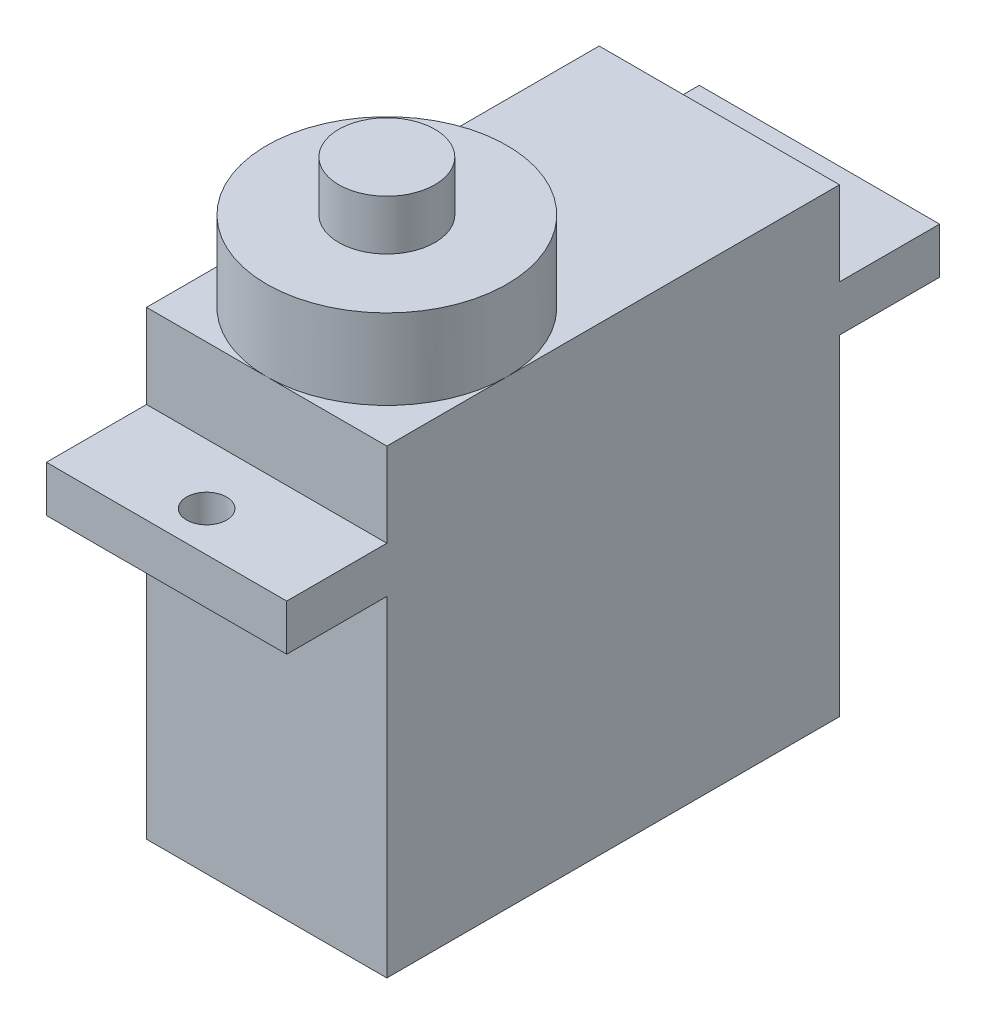
SolidWorks part; units mm, degrees
ref_plane "Front Plane" through (0, 0, 0) normal (0, 0, 1) x (1, 0, 0)
ref_plane "Top Plane" through (0, 0, 0) normal (0, 1, 0) x (1, 0, 0)
ref_plane "Right Plane" through (0, 0, 0) normal (1, 0, 0) x (0, 0, -1)
sketch "Sketch1" plane through (0, 0, 0) normal (1, 0, 0) x (0, 0, -1)
  line L1 (0, 0) -> (22.6, 0)
  line L2 (0, 0) -> (0, 23)
  line L3 (0, 23) -> (22.6, 23)
  line L4 (22.6, 0) -> (22.6, 23)
  dimension "D1" = 23
  dimension "D2" = 22.6
extrude "Boss-Extrude1" add sketch "Sketch1" along normal blind 12
sketch "Sketch2" plane through (0, 23, 0) normal (0, 1, 0) x (1, 0, 0)
  line L0 (12, 22.6) -> (12, 0) construction
  line L1 (-6.6, 0) -> (6.6, 0) construction
  circle A0 centre (6, 6) radius 6
  dimension "D1" = 12
  dimension "D3" = 6
  dimension "D2" = 6
extrude "Boss-Extrude2" add sketch "Sketch2" along normal blind 4
sketch "Sketch3" plane through (0, 27, 0) normal (0, 1, 0) x (1, 0, 0)
  circle A0 centre (6, 6) radius 2.4
  dimension "D1" = 4.8
extrude "Boss-Extrude3" add sketch "Sketch3" along normal blind 2.5
ref_plane "Plane1" through (0, 16.5, 0) normal (0, 1, 0) x (1, 0, 0)
sketch "Sketch4" plane through (0, 16.5, 0) normal (0, 1, 0) x (1, 0, 0)
  line L0 (-6.6, 0) -> (6.6, 0) construction
  line L1 (12, 0) -> (0, 0)
  line L2 (12, 0) -> (12, -5)
  line L3 (12, -5) -> (0, -5)
  line L4 (0, 0) -> (0, -5)
  line L5 (12, 0) -> (12, 22.6) construction
  line L6 (0, -12.43) -> (0, 12.43) construction
  line L7 (0, 22.6) -> (12, 22.6)
  line L8 (0, 22.6) -> (0, 27.6)
  line L9 (0, 27.6) -> (12, 27.6)
  line L10 (12, 22.6) -> (12, 27.6)
  line L11 (12, 22.6) -> (0, 22.6) construction
  circle A0 centre (6, -3) radius 1
  circle A1 centre (6, 25.6) radius 1
  dimension "D2" = 2
  dimension "D3" = 6
  dimension "D4" = 2
  dimension "D5" = 2
  dimension "D6" = 2
  dimension "D7" = 6
  dimension "D1" = 5
extrude "Boss-Extrude4" add sketch "Sketch4" along normal blind 2.3
